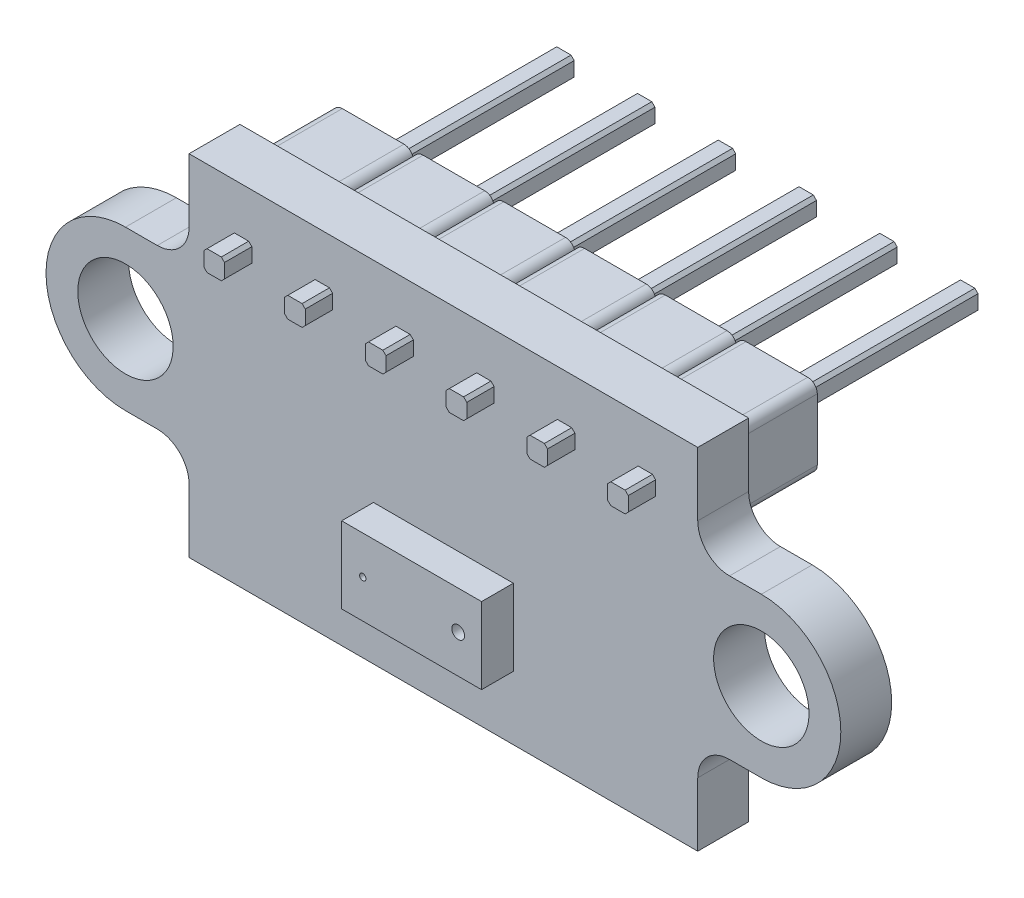
SolidWorks part; units mm, degrees
ref_plane "Alzado" through (0, 0, 0) normal (0, 0, 1) x (1, 0, 0)
ref_plane "Planta" through (0, 0, 0) normal (0, 1, 0) x (1, 0, 0)
ref_plane "Vista lateral" through (0, 0, 0) normal (1, 0, 0) x (0, 0, -1)
sketch "Croquis1" plane through (0, 0, 0) normal (0, 0, 1) x (1, 0, 0)
  line L0 (-12.5, 0) -> (12.5, 0) construction
  line L1 (-8, -5.5) -> (8, -5.5)
  line L2 (-8, -5.5) -> (-8, -2.5)
  line L3 (-8, 5.5) -> (8, 5.5)
  line L4 (8, -5.5) -> (8, -2.5)
  line L5 (-8, -5.5) -> (8, 5.5) construction
  line L6 (-8, 5.5) -> (8, -5.5) construction
  line L8 (10, 2.5) -> (8, 2.5)
  line L9 (10, -2.5) -> (8, -2.5)
  line L10 (8, 2.5) -> (8, 5.5)
  line L11 (-10, -2.5) -> (-8, -2.5)
  line L12 (-10, 2.5) -> (-8, 2.5)
  line L13 (-8, 2.5) -> (-8, 5.5)
  arc A0 (10, -2.5) -> (10, 2.5) centre (10, 0) ccw
  circle A1 centre (10, 0) radius 1.5
  arc A4 (-10, -2.5) -> (-10, 2.5) centre (-10, 0) cw
  circle A5 centre (-10, 0) radius 1.5
  point P0 (0, 0)
  point P9 (0, 0)
  dimension "D4" = 5
  dimension "D5" = 3
  dimension "D6" = 2.5
  dimension "D1" = 16
  dimension "D2" = 11
  dimension "D3" = 25
extrude "Saliente-Extruir1" add sketch "Croquis1" along normal blind 1.6
sketch "Croquis2" plane through (0, 0, 1.6) normal (0, 0, 1) x (1, 0, 0)
  line L6 (0, 0) -> (0, -5.5) construction
  line L7 (-8, -5.5) -> (8, -5.5) construction
  line L8 (8, 5.5) -> (-8, 5.5) construction
  line L9 (-2.2, -3.5) -> (2.2, -3.5)
  line L10 (-2.2, -3.5) -> (-2.2, -1.1)
  line L11 (-2.2, -1.1) -> (2.2, -1.1)
  line L12 (2.2, -3.5) -> (2.2, -1.1)
  line L13 (-2.2, -3.5) -> (2.2, -1.1) construction
  line L14 (-2.2, -1.1) -> (2.2, -3.5) construction
  line L15 (-2.2, -2.3) -> (2.2, -2.3) construction
  circle A0 centre (-1.535, -2.3) radius 0.1
  circle A1 centre (1.465, -2.3) radius 0.2
  point P4 (0, -2.3)
  dimension "D4" = 0.2
  dimension "D5" = 0.4
  dimension "D1" = 9
  dimension "D2" = 2.4
  dimension "D3" = 4.4
  dimension "D6" = 0.665
  dimension "D7" = 3
extrude "Saliente-Extruir2" add sketch "Croquis2" along normal blind 1
fillet "Redondeo1" radius 1 4 edges at (-8, 2.5, 0.8) (-8, -2.5, 0.8) (8, -2.5, 0.8) (8, 2.5, 0.8)
sketch "Croquis3" plane through (0, 0, 0) normal (0, 0, -1) x (-1, 0, 0)
  line L0 (0, 0) -> (0, 2.76) construction
  line L1 (-8, 5.5) -> (8, 5.5) construction
  line L3 (0.3, 2.46) -> (2.24, 2.46)
  line L5 (0.3, 5) -> (2.24, 5)
  line L55 (5.38, 2.46) -> (7.32, 2.46)
  line L56 (7.62, 2.76) -> (7.62, 4.7)
  line L57 (5.38, 5) -> (7.32, 5)
  line L63 (2.84, 2.46) -> (4.78, 2.46)
  line L65 (2.84, 5) -> (4.78, 5)
  line L75 (-4.78, 2.46) -> (-2.84, 2.46)
  line L77 (-4.78, 5) -> (-2.84, 5)
  line L83 (-2.24, 2.46) -> (-0.3, 2.46)
  line L85 (-2.24, 5) -> (-0.3, 5)
  line L90 (-7.62, 2.76) -> (-7.62, 4.7)
  line L91 (-7.32, 2.46) -> (-5.38, 2.46)
  line L93 (-7.32, 5) -> (-5.38, 5)
  line L95 (-2.24, 5) -> (-0.3, 5) [skipped]
  line L97 (-2.24, 2.46) -> (-0.3, 2.46) [skipped]
  line L99 (-4.78, 5) -> (-2.84, 5) [skipped]
  line L101 (-4.78, 2.46) -> (-2.84, 2.46) [skipped]
  line L103 (0.3, 5) -> (2.24, 5) [skipped]
  line L105 (0.3, 2.46) -> (2.24, 2.46) [skipped]
  line L107 (2.84, 5) -> (4.78, 5) [skipped]
  line L109 (2.84, 2.46) -> (4.78, 2.46) [skipped]
  line L111 (0.3, 5) -> (2.24, 5) [skipped]
  line L113 (0.3, 2.46) -> (2.24, 2.46) [skipped]
  line L115 (-2.24, 5) -> (-0.3, 5) [skipped]
  line L117 (-2.24, 2.46) -> (-0.3, 2.46) [skipped]
  line L125 (0, 4.7) -> (0, 5.5) construction
  arc A0 (2.54, 2.76) -> (2.24, 2.46) centre (2.24, 2.76) cw
  arc A1 (0.3, 2.46) -> (0, 2.76) centre (0.3, 2.76) cw
  arc A2 (2.54, 4.7) -> (2.24, 5) centre (2.24, 4.7) ccw
  arc A52 (5.38, 5) -> (5.08, 4.7) centre (5.38, 4.7) ccw
  arc A53 (5.38, 2.46) -> (5.08, 2.76) centre (5.38, 2.76) cw
  arc A54 (7.62, 2.76) -> (7.32, 2.46) centre (7.32, 2.76) cw
  arc A55 (7.62, 4.7) -> (7.32, 5) centre (7.32, 4.7) ccw
  arc A60 (2.84, 5) -> (2.54, 4.7) centre (2.84, 4.7) ccw
  arc A61 (2.84, 2.46) -> (2.54, 2.76) centre (2.84, 2.76) cw
  arc A62 (5.08, 2.76) -> (4.78, 2.46) centre (4.78, 2.76) cw
  arc A63 (5.08, 4.7) -> (4.78, 5) centre (4.78, 4.7) ccw
  arc A72 (-4.78, 5) -> (-5.08, 4.7) centre (-4.78, 4.7) ccw
  arc A73 (-4.78, 2.46) -> (-5.08, 2.76) centre (-4.78, 2.76) cw
  arc A74 (-2.54, 2.76) -> (-2.84, 2.46) centre (-2.84, 2.76) cw
  arc A75 (-2.54, 4.7) -> (-2.84, 5) centre (-2.84, 4.7) ccw
  arc A80 (-2.24, 5) -> (-2.54, 4.7) centre (-2.24, 4.7) ccw
  arc A81 (-2.24, 2.46) -> (-2.54, 2.76) centre (-2.24, 2.76) cw
  arc A82 (0, 2.76) -> (-0.3, 2.46) centre (-0.3, 2.76) cw
  arc A88 (-7.32, 5) -> (-7.62, 4.7) centre (-7.32, 4.7) ccw
  arc A89 (-7.32, 2.46) -> (-7.62, 2.76) centre (-7.32, 2.76) cw
  arc A90 (-5.08, 2.76) -> (-5.38, 2.46) centre (-5.38, 2.76) cw
  arc A91 (-5.08, 4.7) -> (-5.38, 5) centre (-5.38, 4.7) ccw
  arc A93 (0, 4.7) -> (-0.3, 5) centre (-0.3, 4.7) ccw [skipped]
  arc A94 (0, 2.76) -> (-0.3, 2.46) centre (-0.3, 2.76) cw [skipped]
  arc A95 (-2.24, 2.46) -> (-2.54, 2.76) centre (-2.24, 2.76) cw [skipped]
  arc A97 (-2.54, 4.7) -> (-2.84, 5) centre (-2.84, 4.7) ccw [skipped]
  arc A98 (-2.54, 2.76) -> (-2.84, 2.46) centre (-2.84, 2.76) cw [skipped]
  arc A99 (-4.78, 2.46) -> (-5.08, 2.76) centre (-4.78, 2.76) cw [skipped]
  arc A101 (2.54, 4.7) -> (2.24, 5) centre (2.24, 4.7) ccw [skipped]
  arc A102 (2.54, 2.76) -> (2.24, 2.46) centre (2.24, 2.76) cw [skipped]
  arc A103 (0.3, 2.46) -> (0, 2.76) centre (0.3, 2.76) cw [skipped]
  arc A105 (5.08, 4.7) -> (4.78, 5) centre (4.78, 4.7) ccw [skipped]
  arc A106 (5.08, 2.76) -> (4.78, 2.46) centre (4.78, 2.76) cw [skipped]
  arc A107 (2.84, 2.46) -> (2.54, 2.76) centre (2.84, 2.76) cw [skipped]
  arc A109 (2.54, 4.7) -> (2.24, 5) centre (2.24, 4.7) ccw [skipped]
  arc A110 (2.54, 2.76) -> (2.24, 2.46) centre (2.24, 2.76) cw [skipped]
  arc A111 (0.3, 2.46) -> (0, 2.76) centre (0.3, 2.76) cw [skipped]
  arc A113 (0, 4.7) -> (-0.3, 5) centre (-0.3, 4.7) ccw [skipped]
  arc A114 (0, 2.76) -> (-0.3, 2.46) centre (-0.3, 2.76) cw [skipped]
  arc A115 (-2.24, 2.46) -> (-2.54, 2.76) centre (-2.24, 2.76) cw [skipped]
  arc A116 (0, 4.7) -> (-0.3, 5) centre (-0.3, 4.7) ccw [skipped]
  arc A117 (0, 4.7) -> (-0.3, 5) centre (-0.3, 4.7) ccw
  arc A118 (0.3, 5) -> (0, 4.7) centre (0.3, 4.7) ccw
  point P9 (1.27, 5)
  point P12 (2.54, 2.46)
  point P15 (0, 2.46)
  point P18 (2.54, 5)
  point P21 (0, 5)
  dimension "D4" = 0.3
  dimension "D1" = 2.54
  dimension "D3" = 0.5
  dimension "D5" = 3
  dimension "D6" = 4
extrude "Saliente-Extruir3" add sketch "Croquis3" along normal blind 2.54
sketch "Croquis4" plane through (0, 0, -2.54) normal (0, 0, -1) x (-1, 0, 0)
  line L0 (1.27, 5) -> (1.27, 2.46) construction
  line L1 (2.24, 5) -> (0.3, 5) construction
  line L2 (0.3, 2.46) -> (2.24, 2.46) construction
  line L8 (0.945, 3.405) -> (1.595, 4.055) construction
  line L9 (0.945, 4.055) -> (1.595, 3.405) construction
  line L13 (6.025, 3.505) -> (6.025, 3.955)
  line L14 (6.125, 3.405) -> (6.575, 3.405)
  line L15 (6.675, 3.505) -> (6.675, 3.955)
  line L16 (6.125, 4.055) -> (6.575, 4.055)
  line L21 (3.485, 3.505) -> (3.485, 3.955)
  line L22 (3.585, 3.405) -> (4.035, 3.405)
  line L23 (4.135, 3.505) -> (4.135, 3.955)
  line L24 (3.585, 4.055) -> (4.035, 4.055)
  line L29 (0.945, 3.505) -> (0.945, 3.955)
  line L30 (1.045, 3.405) -> (1.495, 3.405)
  line L31 (1.595, 3.505) -> (1.595, 3.955)
  line L32 (1.045, 4.055) -> (1.495, 4.055)
  line L33 (-4.135, 3.505) -> (-4.135, 3.955)
  line L34 (-4.035, 3.405) -> (-3.585, 3.405)
  line L35 (-3.485, 3.505) -> (-3.485, 3.955)
  line L36 (-4.035, 4.055) -> (-3.585, 4.055)
  line L41 (-1.595, 3.505) -> (-1.595, 3.955)
  line L42 (-1.495, 3.405) -> (-1.045, 3.405)
  line L43 (-0.945, 3.505) -> (-0.945, 3.955)
  line L44 (-1.495, 4.055) -> (-1.045, 4.055)
  line L49 (-6.675, 3.505) -> (-6.675, 3.955)
  line L50 (-6.575, 3.405) -> (-6.125, 3.405)
  line L51 (-6.025, 3.505) -> (-6.025, 3.955)
  line L52 (-6.575, 4.055) -> (-6.125, 4.055)
  line L69 (-6.675, 3.955) -> (-6.575, 4.055)
  line L70 (-6.125, 4.055) -> (-6.025, 3.955)
  line L71 (-6.125, 3.405) -> (-6.025, 3.505)
  line L72 (-6.675, 3.505) -> (-6.575, 3.405)
  line L73 (-4.135, 3.505) -> (-4.035, 3.405)
  line L74 (-4.135, 3.955) -> (-4.035, 4.055)
  line L75 (-3.485, 3.955) -> (-3.585, 4.055)
  line L76 (-3.585, 3.405) -> (-3.485, 3.505)
  line L77 (-1.595, 3.955) -> (-1.495, 4.055)
  line L78 (-0.945, 3.955) -> (-1.045, 4.055)
  line L79 (-1.045, 3.405) -> (-0.945, 3.505)
  line L80 (-1.495, 3.405) -> (-1.595, 3.505)
  line L81 (0.945, 3.955) -> (1.045, 4.055)
  line L82 (1.495, 4.055) -> (1.595, 3.955)
  line L83 (1.495, 3.405) -> (1.595, 3.505)
  line L84 (0.945, 3.505) -> (1.045, 3.405)
  line L85 (4.035, 4.055) -> (4.135, 3.955)
  line L86 (4.035, 3.405) -> (4.135, 3.505)
  line L87 (3.585, 3.405) -> (3.485, 3.505)
  line L88 (3.485, 3.955) -> (3.585, 4.055)
  line L89 (6.025, 3.955) -> (6.125, 4.055)
  line L90 (6.025, 3.505) -> (6.125, 3.405)
  line L91 (6.575, 4.055) -> (6.675, 3.955)
  line L92 (6.575, 3.405) -> (6.675, 3.505)
  point P6 (1.27, 3.73)
  point P18 (6.675, 4.055)
  point P19 (6.025, 3.405)
  point P20 (6.025, 4.055)
  point P21 (6.675, 3.405)
  point P26 (4.135, 4.055)
  point P27 (3.485, 3.405)
  point P28 (3.485, 4.055)
  point P29 (4.135, 3.405)
  point P34 (1.595, 4.055)
  point P35 (0.945, 3.405)
  point P36 (0.945, 4.055)
  point P37 (1.595, 3.405)
  point P38 (-3.485, 4.055)
  point P39 (-4.135, 3.405)
  point P40 (-4.135, 4.055)
  point P41 (-3.485, 3.405)
  point P46 (-0.945, 4.055)
  point P47 (-1.595, 3.405)
  point P48 (-1.595, 4.055)
  point P49 (-0.945, 3.405)
  point P54 (-6.025, 4.055)
  point P55 (-6.675, 3.405)
  point P56 (-6.675, 4.055)
  point P57 (-6.025, 3.405)
  dimension "D1" = 0.65
  dimension "D2" = 0.65
extrude "Saliente-Extruir4" add sketch "Croquis4" along normal blind 6 and the other way blind 5
sketch "Croquis5" plane through (0, 0, 1.6) normal (0, 0, 1) x (1, 0, 0)
  circle A0 centre (-10, 0) radius 1.5
  circle A1 centre (10, 0) radius 1.5
